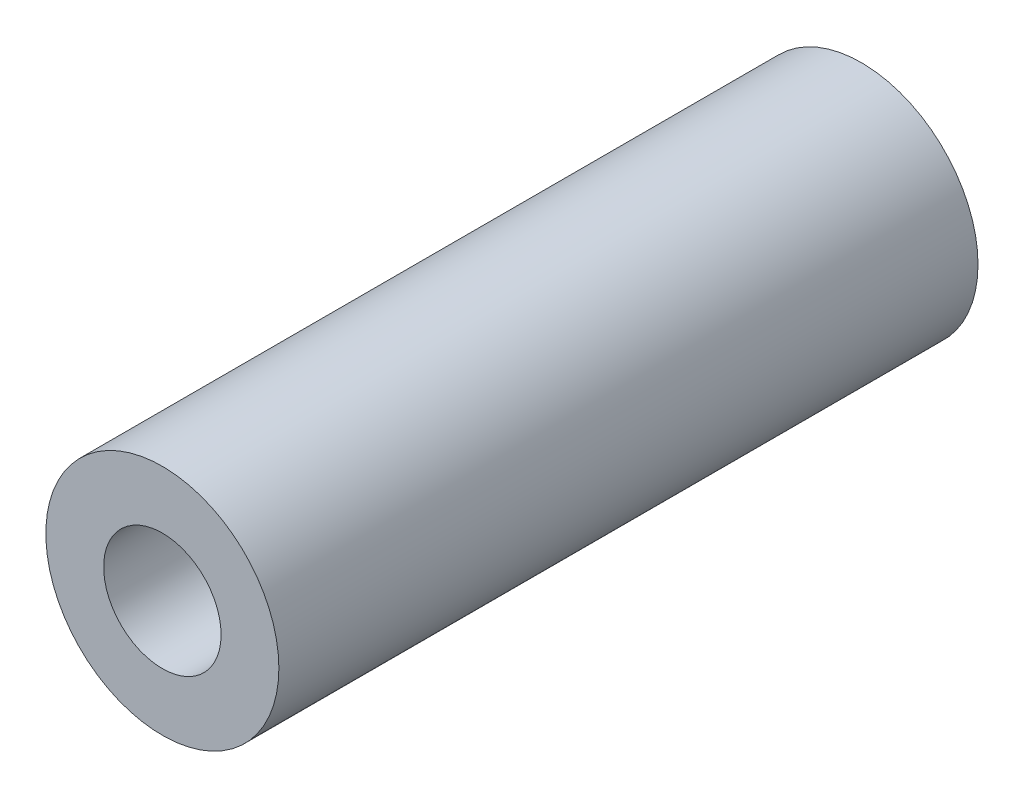
SolidWorks part; units mm, degrees
ref_plane "Front Plane" through (0, 0, 0) normal (0, 0, 1) x (1, 0, 0)
ref_plane "Top Plane" through (0, 0, 0) normal (0, 1, 0) x (1, 0, 0)
ref_plane "Right Plane" through (0, 0, 0) normal (1, 0, 0) x (0, 0, -1)
sketch "Sketch1" plane through (0, 0, 0) normal (0, 0, 1) x (1, 0, 0)
  circle A0 centre (0, 0) radius 6.35 construction
  circle A1 centre (0, 0) radius 3.2004 construction
  point P4 (0, 6.35)
  dimension "ID" = 6.4008
  dimension "OD" = 12.7
sketch "Sketch2" plane through (0, 0, 0) normal (1, 0, 0) x (0, 0, -1)
  line L0 (-152.4, 6.35) -> (152.4, 6.35) construction
  point P2 (136.525, 6.35)
  point P3 (-136.525, 6.35)
  dimension "Length" = 304.8
  dimension "D1" = 15.875
  dimension "D2" = 15.875
sketch "Sketch3" plane through (0, 0, 0) normal (0, 0, 1) x (1, 0, 0)
  circle A0 centre (0, 0) radius 3.2004 construction
  circle A1 centre (0, 0) radius 6.35 construction
  circle A2 centre (0, 0) radius 3.2004
  circle A3 centre (0, 0) radius 6.35
extrude "Boss-Extrude1" add sketch "Sketch3" against normal up to vertex (152.4 mm away) and the other way up to vertex (152.4 mm away) up to point (0, 6.35, -152.4) other way up to point (0, 6.35, 152.4)
sketch "Sketch4" plane through (0, 0, 152.4) normal (0, 0, 1) x (1, 0, 0)
  circle A0 centre (0, 0) radius 25.4
extrude "Cut-Extrude1" cut sketch "Sketch4" against normal blind 266.7
equation "\"D1@Sketch2\"=\"OD@Sketch1\"*1.25"
equation "\"D2@Sketch2\"=\"D1@Sketch2\""
